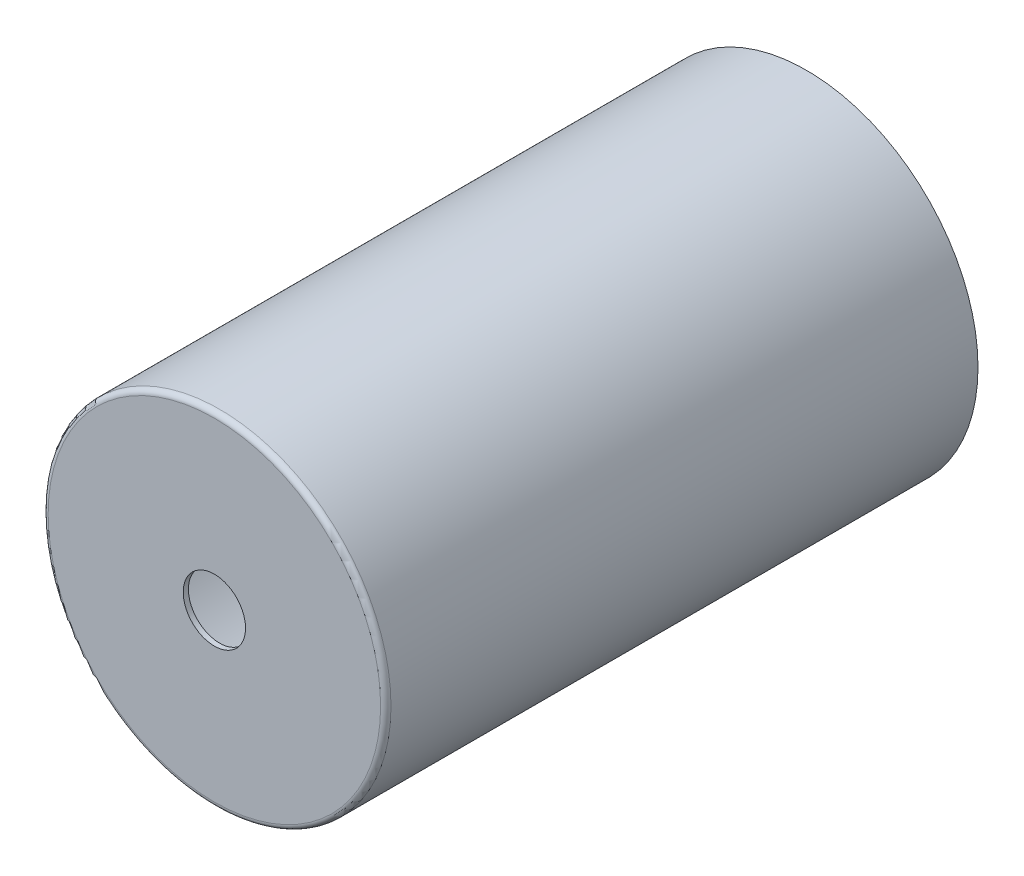
SolidWorks part; units mm, degrees
ref_plane "Front Plane" through (0, 0, 0) normal (0, 0, 1) x (1, 0, 0)
ref_plane "Top Plane" through (0, 0, 0) normal (0, 1, 0) x (1, 0, 0)
ref_plane "Right Plane" through (0, 0, 0) normal (1, 0, 0) x (0, 0, -1)
sketch "Sketch1" plane through (0, 0, 0) normal (0, 0, 1) x (1, 0, 0)
  circle A0 centre (0, 0) radius 16.5
  dimension "D1" = 33
extrude "Boss-Extrude1" add sketch "Sketch1" against normal blind 57
shell "Shell1" thickness 0.5
sketch "Sketch2" plane through (0, 0, 0) normal (0, 0, 1) x (1, 0, 0)
  circle A0 centre (0, 0) radius 3
  dimension "D1" = 6
extrude "Cut-Extrude1" cut sketch "Sketch2" against normal through all
fillet "Fillet1" radius 0.5 1 edges at (16.5, 0, 0)
